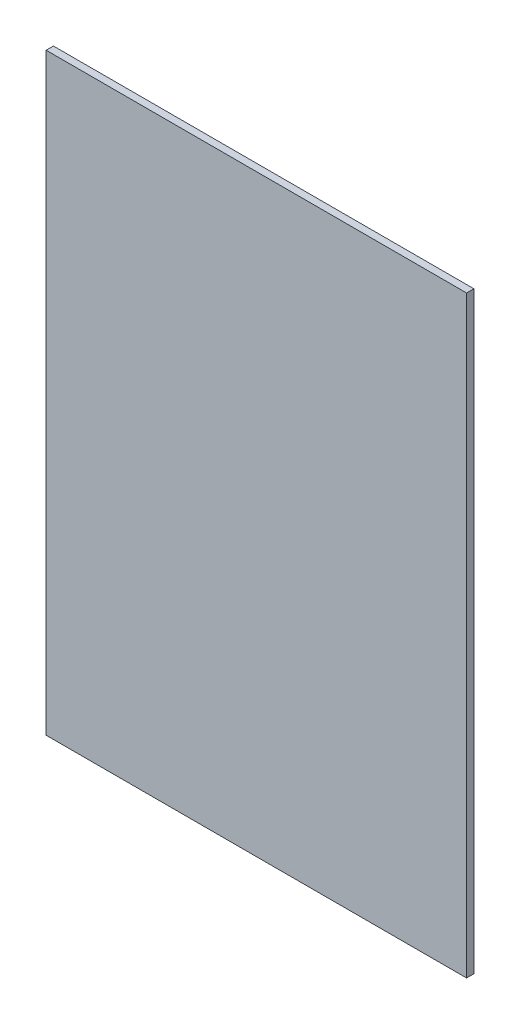
SolidWorks part; units mm, degrees
ref_plane "Front Plane" through (0, 0, 0) normal (0, 0, 1) x (1, 0, 0)
ref_plane "Top Plane" through (0, 0, 0) normal (0, 1, 0) x (1, 0, 0)
ref_plane "Right Plane" through (0, 0, 0) normal (1, 0, 0) x (0, 0, -1)
sketch "Sketch1" plane through (0, 0, 0) normal (0, 0, 1) x (1, 0, 0)
  line L1 (0, 0) -> (172.8, 0)
  line L2 (0, 0) -> (0, 243.83)
  line L3 (0, 243.83) -> (172.8, 243.83)
  line L4 (172.8, 0) -> (172.8, 243.83)
  dimension "D1" = 172.8
  dimension "D2" = 243.83
extrude "Boss-Extrude1" add sketch "Sketch1" along normal blind 3
